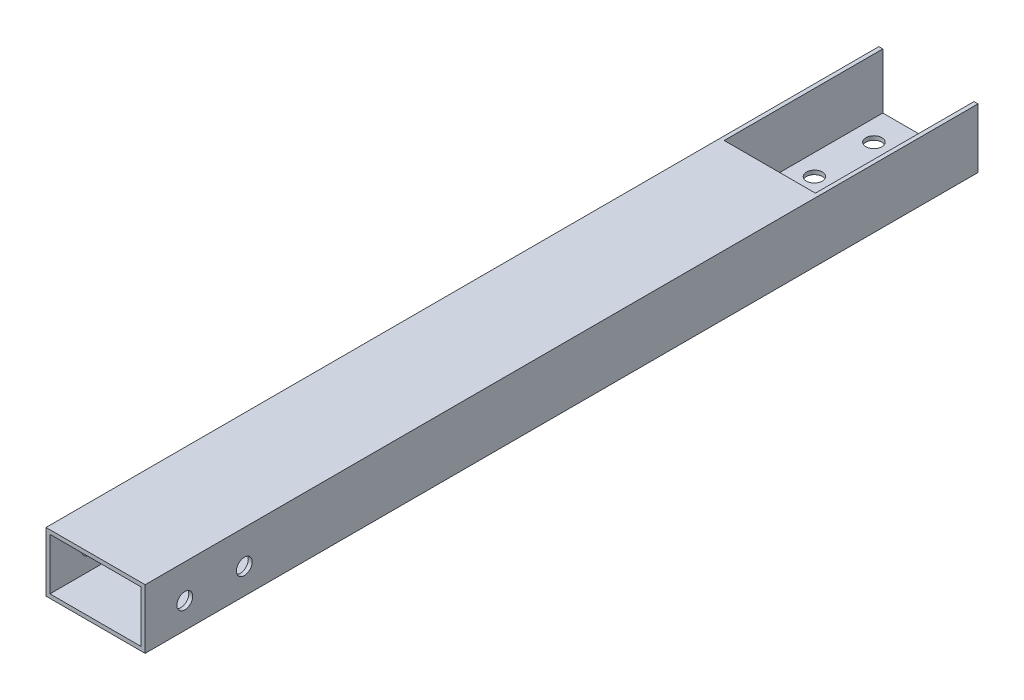
SolidWorks part; units mm, degrees
material "1023 Carbon Steel Sheet (SS)"
ref_plane "Front Plane" through (0, 0, 0) normal (0, 0, 1) x (1, 0, 0)
ref_plane "Top Plane" through (0, 0, 0) normal (0, 1, 0) x (1, 0, 0)
ref_plane "Right Plane" through (0, 0, 0) normal (1, 0, 0) x (0, 0, -1)
sketch "Sketch1" plane through (0, 0, 0) normal (0, 0, 1) x (1, 0, 0)
  line L0 (2, -2) -> (48, -2)
  line L1 (0, 0) -> (50, 0)
  line L2 (0, 0) -> (0, -30)
  line L3 (0, -30) -> (50, -30)
  line L4 (50, 0) -> (50, -30)
  line L5 (48, -2) -> (48, -28)
  line L6 (2, -28) -> (48, -28)
  line L7 (2, -2) -> (2, -28)
  dimension "D1" = 50
  dimension "D2" = 30
  dimension "D3" = 2
extrude "Boss-Extrude1" add sketch "Sketch1" along normal blind 420
sketch "Sketch7" plane through (0, -28, 0) normal (0, 1, 0) x (1, 0, 0)
  line L2 (2, 0) -> (48, 0) construction
  line L3 (50, -420) -> (50, 0) construction
  line L4 (0, -420) -> (0, 0) construction
  circle A0 centre (37.5, -45) radius 4
  circle A1 centre (12.5, -45) radius 4
  circle A2 centre (12.5, -15) radius 4
  circle A3 centre (37.5, -15) radius 4
  dimension "D1" = 8
  dimension "D2" = 8
  dimension "D3" = 8
  dimension "D4" = 8
  dimension "D5" = 25
  dimension "D6" = 12.5
  dimension "D7" = 12.5
  dimension "D8" = 12.5
  dimension "D9" = 25
  dimension "D10" = 15
  dimension "D11" = 15
  dimension "D12" = 30
extrude "Cut-Extrude2" cut sketch "Sketch7" against normal through all
sketch "Sketch8" plane through (50, 0, 0) normal (1, 0, 0) x (0, 0, -1)
  line L0 (-420, -30) -> (0, -30) construction
  line L1 (-420, -30) -> (-420, 0) construction
  circle A0 centre (-400, -17) radius 4
  circle A1 centre (-370, -17) radius 4
  dimension "D1" = 8
  dimension "D2" = 8
  dimension "D3" = 13
  dimension "D5" = 20
  dimension "D6" = 50
  dimension "D4" = 13
extrude "Cut-Extrude3" cut sketch "Sketch8" against normal through all
sketch "Sketch9" plane through (0, 0, 0) normal (0, 1, 0) x (1, 0, 0)
  line L0 (2, 0) -> (48, 0)
  line L1 (48, 0) -> (48, -80)
  line L3 (48, -80) -> (2, -80)
  line L5 (2, -80) -> (2, 0)
  line L6 (0, -420) -> (0, 0) construction
  dimension "D1" = 80
  dimension "D2" = 46
  dimension "D3" = 2
extrude "Cut-Extrude4" cut sketch "Sketch9" against normal up to next
